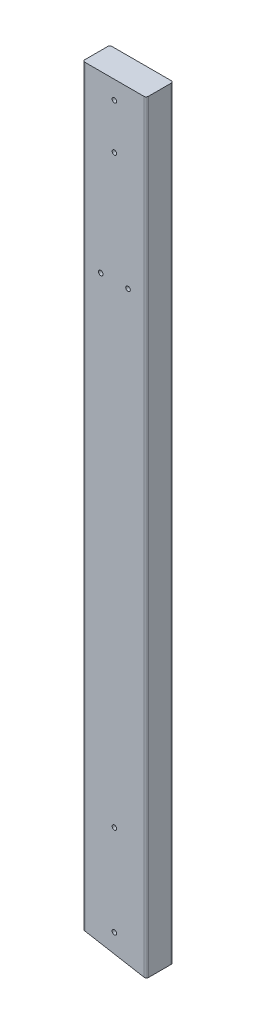
SolidWorks part; units mm, degrees
ref_plane "Front" through (0, 0, 0) normal (0, 0, 1) x (1, 0, 0)
ref_plane "Top" through (0, 0, 0) normal (0, 1, 0) x (1, 0, 0)
ref_plane "Right" through (0, 0, 0) normal (1, 0, 0) x (0, 0, -1)
sketch "Sketch1" plane through (0, 0, 0) normal (0, 1, 0) x (1, 0, 0)
  line L1 (44.45, 19.05) -> (-44.45, 19.05)
  line L2 (44.45, 19.05) -> (44.45, -19.05)
  line L3 (44.45, -19.05) -> (-44.45, -19.05)
  line L4 (-44.45, 19.05) -> (-44.45, -19.05)
  line L5 (44.45, 19.05) -> (-44.45, -19.05) construction
  line L6 (44.45, -19.05) -> (-44.45, 19.05) construction
  point P0 (0, 0)
  dimension "D1" = 88.9
  dimension "D2" = 38.1
extrude "Boss-Extrude1" add sketch "Sketch1" along normal blind 1068.3875
sketch "Sketch2" plane through (0, 0, 19.05) normal (0, 0, 1) x (1, 0, 0)
  line L0 (44.45, 0) -> (-44.45, 15.6755)
  line L1 (-44.45, 1068.3875) -> (-44.45, 0) construction
  line L2 (-44.45, 15.6755) -> (-44.45, 0)
  line L3 (-44.45, 0) -> (44.45, 0)
  dimension "D1" = 10
extrude "Cut-Extrude1" cut sketch "Sketch2" against normal blind 1257.6368
hole_wizard "1/4 (0.25) Diameter Hole1" positions "Sketch3" profile "Sketch4" hole size "1/4" standard "ANSI Inch" end condition through all
sketch "Sketch3" plane through (0, 0, 19.05) normal (0, 0, 1) x (1, 0, 0)
  line L0 (-44.45, 1068.3875) -> (44.45, 1068.3875) construction
  line L1 (44.45, 1068.3875) -> (44.45, 0) construction
  line L2 (-44.45, 1068.3875) -> (-44.45, 15.6755) construction
  point P0 (0, 34.2253)
  point P3 (0, 161.2253)
  point P6 (19.05, 823.978)
  point P9 (-19.05, 823.978)
  point P12 (0, 979.4875)
  point P15 (0, 1042.9875)
  point P21 (0, 1068.3875)
  dimension "D1" = 25.4
  dimension "D2" = 88.9
  dimension "D3" = 244.4095
  dimension "D4" = 25.4
  dimension "D5" = 25.4
  dimension "D6" = 34.2253
  dimension "D7" = 161.2253
sketch "Sketch4" plane through (0, 34.2253, 19.05) normal (1, 0, 0) x (0, -1, 0)
  line L0 (0, 0) -> (0, 38.1)
  line L1 (0, 38.1) -> (3.175, 38.1)
  line L2 (3.175, 38.1) -> (3.175, 0)
  line L5 (3.175, 0) -> (0, 0)
  line L11 (0, -6.35) -> (0, 107.95) construction
  dimension "Thru Hole Dia." = 6.35
  dimension "Thru Hole Depth" = 38.1
fillet "Fillet1" radius 3.175 4 edges at (-44.45, 542.0315, -19.05) (-44.45, 542.0315, 19.05) (44.45, 534.1938, -19.05) (44.45, 534.1938, 19.05)
